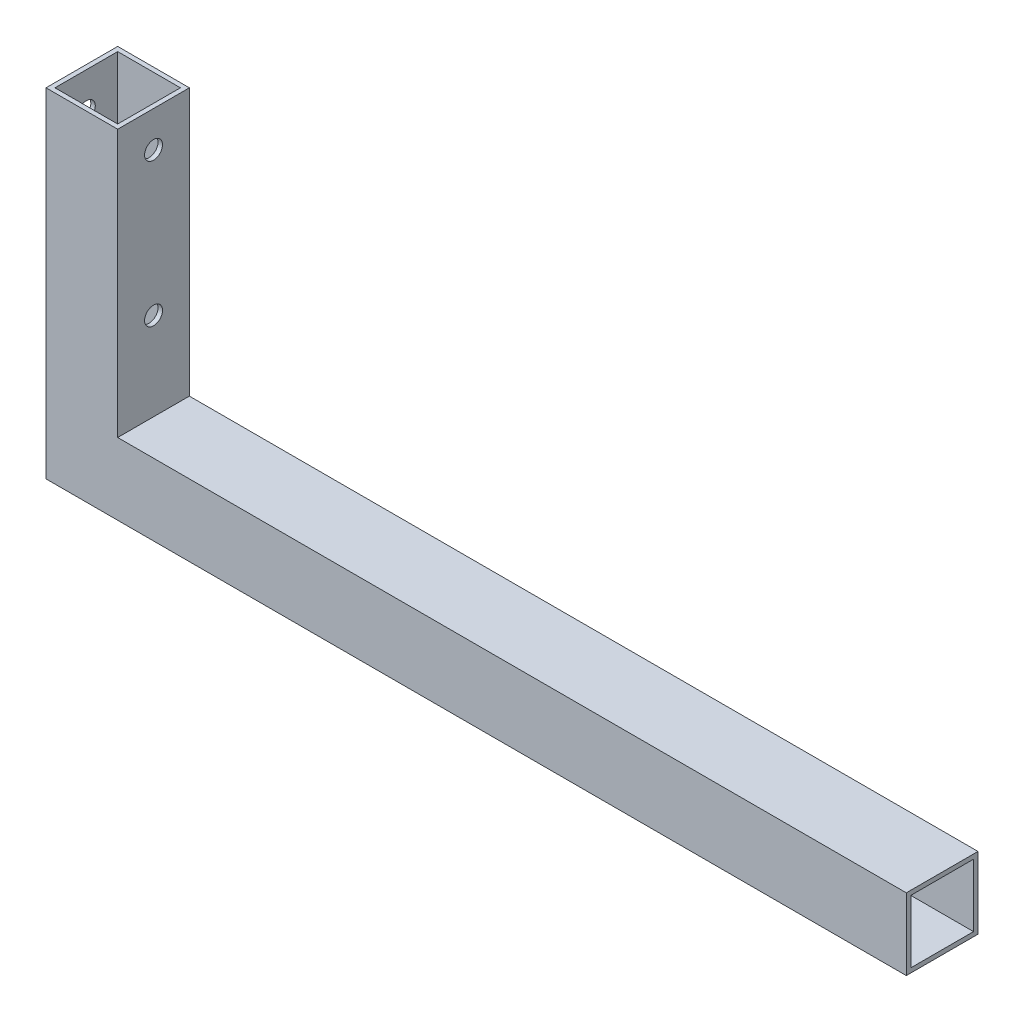
SolidWorks part; units mm, degrees
ref_plane "Front Plane" through (0, 0, 0) normal (0, 0, 1) x (1, 0, 0)
ref_plane "Top Plane" through (0, 0, 0) normal (0, 1, 0) x (1, 0, 0)
ref_plane "Right Plane" through (0, 0, 0) normal (1, 0, 0) x (0, 0, -1)
sketch "Sketch1" plane through (0, 0, 0) normal (0, 1, 0) x (1, 0, 0)
  line L1 (-12.7, 12.7) -> (12.7, 12.7)
  line L2 (-12.7, 12.7) -> (-12.7, -12.7)
  line L3 (-12.7, -12.7) -> (12.7, -12.7)
  line L4 (12.7, 12.7) -> (12.7, -12.7)
  line L5 (-12.7, 12.7) -> (12.7, -12.7) construction
  line L6 (-12.7, -12.7) -> (12.7, 12.7) construction
  line L7 (11.1125, -11.1125) -> (-11.1125, -11.1125)
  line L8 (11.1125, -11.1125) -> (11.1125, 11.1125)
  line L9 (11.1125, 11.1125) -> (-11.1125, 11.1125)
  line L10 (-11.1125, -11.1125) -> (-11.1125, 11.1125)
  line L11 (11.1125, -11.1125) -> (-11.1125, 11.1125) construction
  line L12 (11.1125, 11.1125) -> (-11.1125, -11.1125) construction
  point P0 (0, 0)
  point P6 (0, 0)
  dimension "D1" = 25.4
  dimension "D2" = 1.5875
extrude "Boss-Extrude1" add sketch "Sketch1" along normal blind 228.6
other "1in Square tube<1>"
sketch "Sketch2" plane through (12.7, 0, 0) normal (1, 0, 0) x (0, 0, -1)
  line L0 (0, 228.6) -> (0, 215.9) construction
  line L1 (-12.7, 228.6) -> (12.7, 228.6) construction
  line L2 (0, 215.9) -> (0, 165.1) construction
  circle A0 centre (0, 215.9) radius 3.175
  circle A1 centre (0, 165.1) radius 3.175
  point P7 (0, 228.6)
  dimension "D1" = 6.35
  dimension "D2" = 50.8
  dimension "D3" = 12.7
extrude "Cut-Extrude1" cut sketch "Sketch2" against normal through all
sketch "Sketch3" plane through (0, 0, 12.7) normal (0, 0, 1) x (1, 0, 0)
  line L0 (0, 0) -> (0, 19.05) construction
  line L1 (0, 19.05) -> (0, 69.85) construction
  circle A0 centre (0, 69.85) radius 3.175
  circle A1 centre (0, 19.05) radius 3.175
  dimension "D1" = 6.35
  dimension "D2" = 19.05
  dimension "D3" = 50.8
extrude "Cut-Extrude2" cut sketch "Sketch3" against normal through all
sketch "Sketch4" plane through (0, 0, 12.7) normal (0, 0, 1) x (1, 0, 0)
  line L0 (-12.7, 0) -> (-12.7, 108.6)
  line L1 (-12.7, 228.6) -> (-12.7, 0) construction
  line L2 (-12.7, 108.6) -> (12.7, 134)
  line L3 (12.7, 228.6) -> (12.7, 0) construction
  line L4 (12.7, 134) -> (12.7, 0)
  line L5 (12.7, 0) -> (-12.7, 0)
  dimension "D1" = 120
  dimension "D2" = 45
extrude "Cut-Extrude3" cut sketch "Sketch4" against normal through all
sketch "Sketch6" plane through (12.7, 0, 0) normal (1, 0, 0) x (0, 0, -1)
  line L4 (-12.7, 134) -> (-12.7, 108.6)
  line L5 (-12.7, 108.6) -> (12.7, 108.6)
  line L6 (12.7, 108.6) -> (12.7, 134)
  line L7 (12.7, 134) -> (-12.7, 134)
  line L8 (-12.7, 134) -> (-12.7, 108.6)
  line L9 (-12.7, 108.6) -> (12.7, 108.6)
  line L10 (12.7, 108.6) -> (12.7, 134)
  line L11 (12.7, 134) -> (-12.7, 134)
  line L12 (-11.1125, 110.1875) -> (11.1125, 110.1875)
  line L13 (-11.1125, 132.4125) -> (-11.1125, 110.1875)
  line L14 (11.1125, 132.4125) -> (-11.1125, 132.4125)
  line L15 (11.1125, 110.1875) -> (11.1125, 132.4125)
  line L16 (-11.1125, 110.1875) -> (11.1125, 110.1875)
  line L17 (-11.1125, 132.4125) -> (-11.1125, 110.1875)
  line L18 (11.1125, 132.4125) -> (-11.1125, 132.4125)
  line L19 (11.1125, 110.1875) -> (11.1125, 132.4125)
  dimension "D1" = 0
  dimension "D2" = 0
extrude "Boss-Extrude3" add sketch "Sketch6" along normal blind 279.4 and the other way up to next
